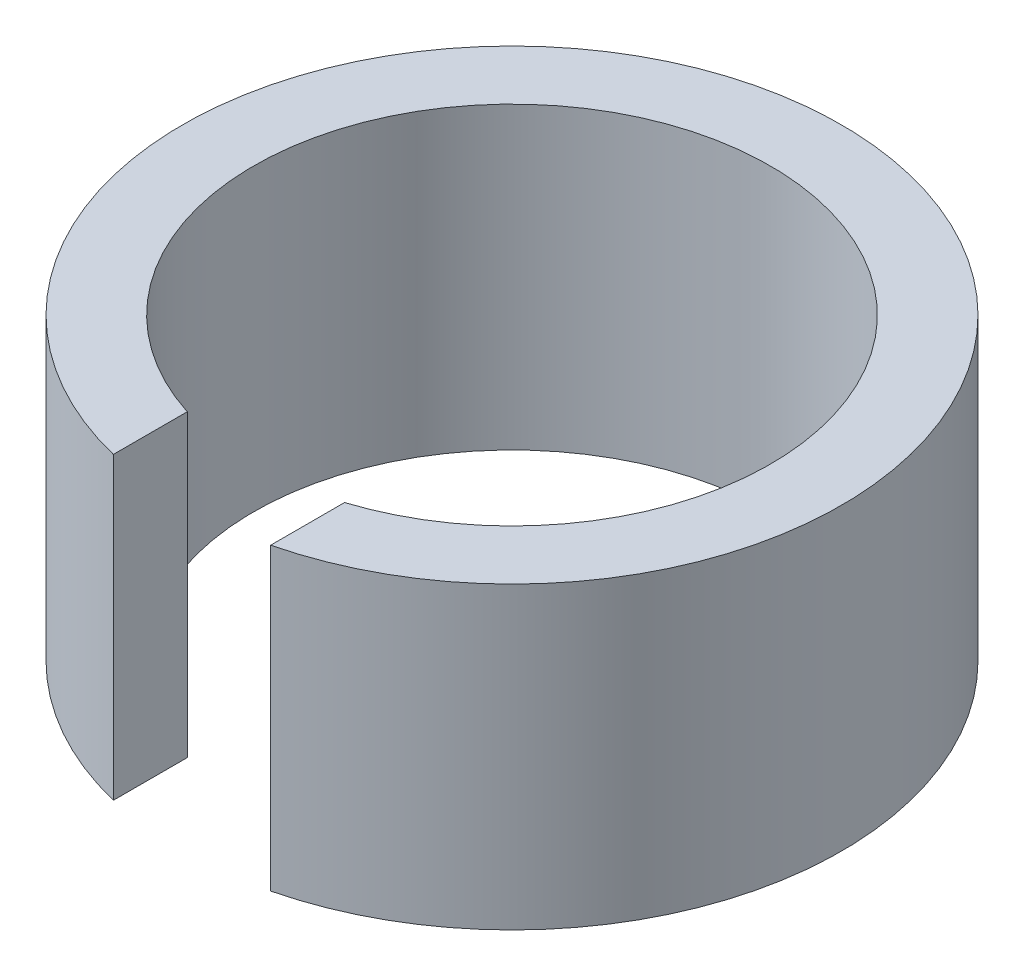
SolidWorks part; units mm, degrees
ref_plane "Front Plane" through (0, 0, 0) normal (0, 0, 1) x (1, 0, 0)
ref_plane "Top Plane" through (0, 0, 0) normal (0, 1, 0) x (1, 0, 0)
ref_plane "Right Plane" through (0, 0, 0) normal (1, 0, 0) x (0, 0, -1)
sketch "Sketch1" plane through (0, 0, 0) normal (0, 1, 0) x (1, 0, 0)
  line L0 (0, 0) -> (0, -3.45) construction
  line L1 (0, -3.45) -> (0, -4.4) construction
  line L3 (-1.05, -3.0135) -> (1.05, -3.0135)
  line L4 (-1.05, -3.0135) -> (-1.05, -4.8365)
  line L5 (-1.05, -4.8365) -> (1.05, -4.8365)
  line L6 (1.05, -3.0135) -> (1.05, -4.8365)
  line L7 (-1.05, -3.0135) -> (1.05, -4.8365) construction
  line L8 (-1.05, -4.8365) -> (1.05, -3.0135) construction
  circle A0 centre (0, 0) radius 3.45
  circle A1 centre (0, 0) radius 4.4
  point P4 (0, -3.925)
  dimension "D1" = 8.8
  dimension "D2" = 6.9
  dimension "D3" = 0.95
  dimension "D4" = 2.1
extrude "Boss-Extrude1" add sketch "Sketch1" along normal blind 4 contours L6 A1 L4 A0
